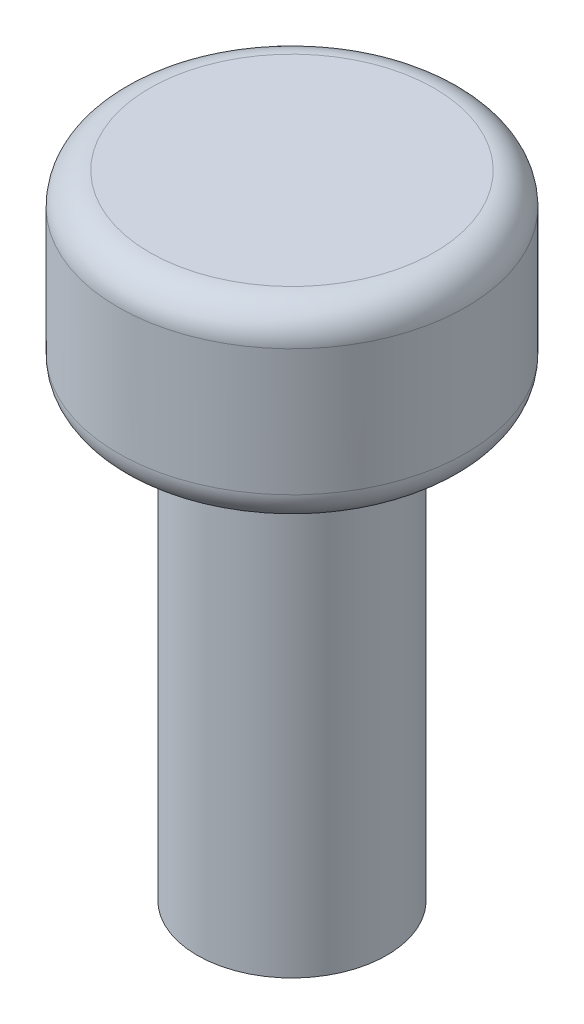
SolidWorks part; units mm, degrees
ref_plane "Front Plane" through (0, 0, 0) normal (0, 0, 1) x (1, 0, 0)
ref_plane "Top Plane" through (0, 0, 0) normal (0, 1, 0) x (1, 0, 0)
ref_plane "Right Plane" through (0, 0, 0) normal (1, 0, 0) x (0, 0, -1)
sketch "Sketch1" plane through (0, 0, 0) normal (0, 0, 1) x (1, 0, 0)
  line L0 (-1.5, 0) -> (1.5, 0) construction
  line L1 (0, 0) -> (1.5, 0)
  line L2 (0, 0) -> (0, 7)
  line L3 (0, 7) -> (1.5, 7) construction
  line L4 (1.5, 0) -> (1.5, 7)
  line L5 (-2.75, 10) -> (2.75, 10) construction
  line L6 (0, 7) -> (2.75, 7) construction
  line L7 (0, 7) -> (0, 10)
  line L8 (0, 10) -> (2.75, 10)
  line L9 (2.75, 7) -> (2.75, 10)
  line L10 (1.5, 7) -> (2.75, 7)
  point P8 (0, 0)
  point P13 (0, 10)
  dimension "D1" = 3
  dimension "D2" = 5.5
  dimension "D3" = 3
  dimension "D4" = 7
revolve "Revolve1" add sketch "Sketch1" angle 360 about L2
fillet "Fillet1" radius 0.5 2 edges at (0, 7, -2.75) (0, 10, -2.75)
